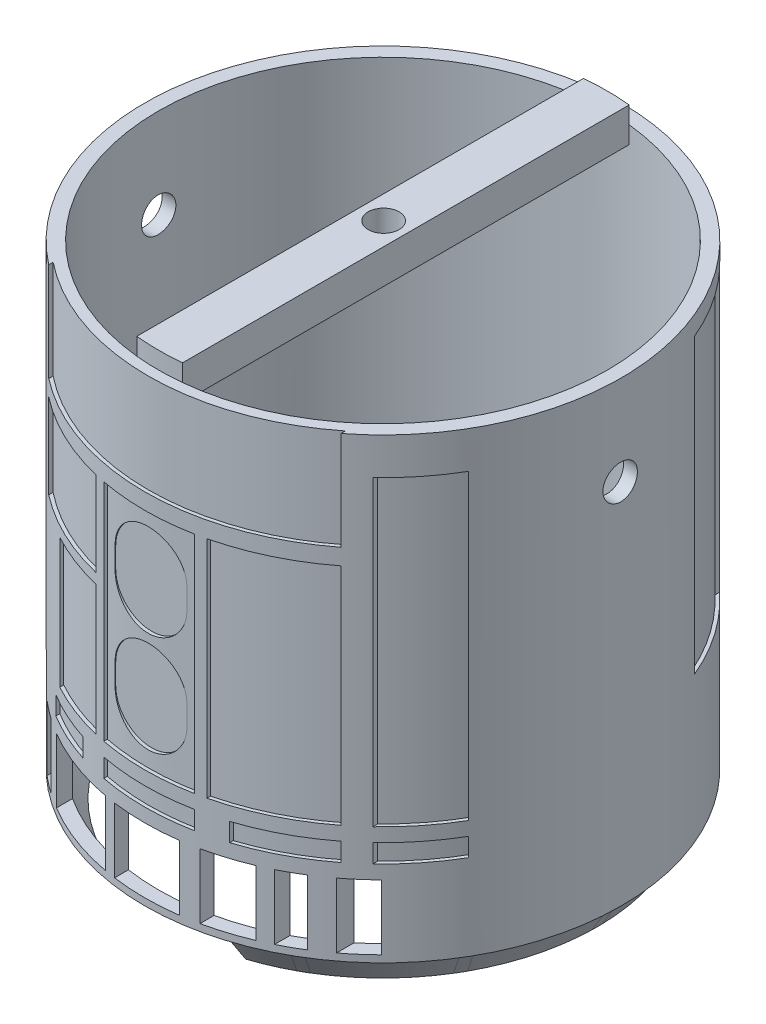
SolidWorks part; units mm, degrees
ref_plane "Front Plane" through (0, 0, 0) normal (0, 0, 1) x (1, 0, 0)
ref_plane "Top Plane" through (0, 0, 0) normal (0, 1, 0) x (1, 0, 0)
ref_plane "Right Plane" through (0, 0, 0) normal (1, 0, 0) x (0, 0, -1)
ref_plane "Plane1" through (0, 71.455, 0) normal (0, -1, 0) x (-1, 0, 0)
sketch "Sketch2" plane through (0, 71.455, 0) normal (0, -1, 0) x (-1, 0, 0)
  line L0 (-38.9651, -35.0313) -> (-38.9651, -151.6617) construction
  line L4 (-38.9651, -105.3401) -> (-38.9651, -128.5901) construction
  line L5 (-163.8451, -151.6283) -> (-163.8451, -35.0647) construction
  line L6 (-163.8451, -58.0901) -> (-163.8451, -81.3401) construction
  arc A2 (-38.9651, -35.0313) -> (-163.8451, -35.0647) centre (-101.3896, -93.3465) ccw construction
  circle A5 centre (-101.2592, -93.1749) radius 81.6374 construction
  circle A6 centre (-101.2592, -93.1749) radius 82.9074
  circle A7 centre (-101.2592, -93.1749) radius 87.9874
  dimension "D1" = 1.27
  dimension "D2" = 5.08
extrude "Boss-Extrude1" add sketch "Sketch2" against normal up to vertex (168.8629 mm away)
sketch "Sketch3" plane through (163.8451, 0, 0) normal (1, 0, 0) x (0, 0, -1)
  line L0 (-146.312, 80.955) -> (-146.312, 71.455) construction
  line L1 (-153.932, 82.225) -> (-107.1601, 82.225)
  line L2 (-153.932, 82.225) -> (-153.932, 68.28)
  line L3 (-153.932, 68.28) -> (-32.7482, 68.28)
  line L4 (-32.7482, 82.225) -> (-32.7482, 68.28)
  line L7 (-40.3682, 71.455) -> (-40.3682, 80.955) construction
  line L8 (-132.7773, 80.955) -> (-144.8088, 80.955) construction
  line L9 (-35.0647, 68.28) -> (-151.6283, 68.28) construction
  line L10 (-79.5201, 82.225) -> (-32.7482, 82.225)
  line L11 (-107.1601, 121.595) -> (-79.5201, 121.595)
  line L12 (-107.1601, 121.595) -> (-107.1601, 82.225)
  line L14 (-79.5201, 121.595) -> (-79.5201, 82.225)
  line L15 (-105.8901, 116.805) -> (-105.8901, 106.605) construction
  line L16 (-80.7901, 116.805) -> (-80.7901, 106.605) construction
  dimension "D1" = 1.27
  dimension "D2" = 7.62
  dimension "D3" = 7.62
  dimension "D4" = 1.27
  dimension "D5" = 1.27
  dimension "D6" = 39.37
extrude "Cut-Extrude1" [suppressed] cut sketch "Sketch3" against normal through all both
sketch "Sketch4" plane through (0, 240.3982, 0) normal (0, 1, 0) x (1, 0, 0)
  circle A2 centre (101.4962, -94.1217) radius 81.1277
  circle A3 centre (101.4962, -94.1217) radius 81.1277
  circle A5 centre (101.4962, -94.1217) radius 84.1757 construction
  dimension "D1" = 5.08
extrude "Cut-Extrude2" [suppressed] cut sketch "Sketch4" against normal through all both
fillet "Fillet1" [suppressed] radius 30.48
ref_plane "Body mid plane" through (101.4051, -9.1621, 1.5034) normal (1, 0, 0) x (0, 0, -1)
sketch "Sketch7" plane through (101.4051, -9.1621, 1.5034) normal (1, 0, 0) x (0, 0, -1)
  line L0 (-5.8069, 80.6171) -> (-12.6369, 69.6961)
  line L1 (-91.8367, 60.9602) -> (-91.8367, 159.3782) construction
  point P5 (-10.4132, 69.2196)
  point P6 (-5.8069, 80.6171)
  point P7 (-12.6369, 69.6961)
  point P9 (-91.8367, 60.9602)
revolve "Revolve-Thin1" add sketch "Sketch7" angle 360 about L1
sketch "Sketch9" plane through (0, 240.318, 0) normal (0, 1, 0) x (1, 0, 0)
  circle A0 centre (101.2592, -93.1749) radius 87.9874 construction
  point P0 (101.2592, -181.1623)
ref_plane "Body front plane" through (101.2592, 240.318, 181.1623) normal (0, 0, 1) x (1, 0, 0)
sketch "Sketch8" plane through (101.2592, 240.318, 181.1623) normal (0, 0, 1) x (1, 0, 0)
  line L1 (-53.975, 0) -> (53.975, 0)
  line L2 (-53.975, 0) -> (-53.975, -36.4031)
  line L3 (-53.975, -36.4031) -> (53.975, -36.4031)
  line L4 (53.975, 0) -> (53.975, -36.4031)
  line L5 (-75.9451, -13.6762) -> (-60.325, -13.6762)
  line L6 (-75.9451, -13.6762) -> (-75.9451, -125.3442)
  line L7 (-75.9451, -125.3442) -> (-60.325, -125.3442)
  line L8 (-60.325, -13.6762) -> (-60.325, -125.3442)
  line L9 (60.325, -13.6762) -> (75.9451, -13.6762)
  line L10 (60.325, -13.6762) -> (60.325, -125.3442)
  line L11 (60.325, -125.3442) -> (75.9451, -125.3442)
  line L12 (75.9451, -13.6762) -> (75.9451, -125.3442)
  line L13 (53.975, -42.3499) -> (20.5317, -42.3499)
  line L14 (53.975, -42.3499) -> (53.975, -125.3442)
  line L15 (53.975, -125.3442) -> (20.5317, -125.3442)
  line L16 (20.5317, -42.3499) -> (20.5317, -125.3442)
  line L17 (-53.975, -42.3499) -> (-20.5317, -42.3499)
  line L18 (-53.975, -42.3499) -> (-53.975, -73.6192)
  line L19 (-53.975, -73.6192) -> (-20.5317, -73.6192)
  line L20 (-20.5317, -42.3499) -> (-20.5317, -73.6192)
  line L21 (-16.7217, -42.3499) -> (16.7217, -42.3499)
  line L22 (-16.7217, -42.3499) -> (-16.7217, -125.3442)
  line L23 (-16.7217, -125.3442) -> (16.7217, -125.3442)
  line L24 (16.7217, -42.3499) -> (16.7217, -125.3442)
  line L25 (-20.5317, -77.3529) -> (-42.14, -77.3529)
  line L26 (-20.5317, -77.3529) -> (-20.5317, -125.3442)
  line L27 (-20.5317, -125.3442) -> (-42.14, -125.3442)
  line L28 (-42.14, -77.3529) -> (-42.14, -125.3442)
  line L29 (60.325, -130.4242) -> (75.9451, -130.4242)
  line L30 (60.325, -130.4242) -> (60.325, -137.2396)
  line L31 (86.2077, 0) -> (-86.2077, 0) construction
  line L33 (60.325, -137.2396) -> (75.9451, -137.2396)
  line L34 (75.9451, -130.4242) -> (75.9451, -137.2396)
  line L35 (53.975, -130.4242) -> (27.0779, -130.4242)
  line L36 (53.975, -130.4242) -> (53.975, -137.2396)
  line L37 (53.975, -137.2396) -> (27.0779, -137.2396)
  line L38 (27.0779, -130.4242) -> (27.0779, -137.2396)
  line L39 (-16.7217, -130.4242) -> (16.7217, -130.4242)
  line L40 (-16.7217, -130.4242) -> (-16.7217, -137.2396)
  line L41 (-16.7217, -137.2396) -> (16.7217, -137.2396)
  line L42 (16.7217, -130.4242) -> (16.7217, -137.2396)
  line L43 (-27.1833, -130.4242) -> (-45.5325, -130.4242)
  line L44 (-27.1833, -130.4242) -> (-27.1833, -137.2396)
  line L45 (-27.1833, -137.2396) -> (-45.5325, -137.2396)
  line L46 (-45.5325, -130.4242) -> (-45.5325, -137.2396)
  line L47 (61.9414, -142.3196) -> (53.0289, -142.3196)
  line L48 (61.9414, -142.3196) -> (61.9414, -166.2789)
  line L49 (61.9414, -166.2789) -> (53.0289, -166.2789)
  line L50 (53.0289, -142.3196) -> (53.0289, -166.2789)
  line L51 (46.7378, -142.3196) -> (38.8738, -142.3196)
  line L52 (46.7378, -142.3196) -> (46.7378, -166.2789)
  line L53 (46.7378, -166.2789) -> (38.8738, -166.2789)
  line L54 (38.8738, -142.3196) -> (38.8738, -166.2789)
  line L55 (18.4276, -142.3196) -> (34.1555, -142.3196)
  line L56 (18.4276, -142.3196) -> (18.4276, -166.2789)
  line L57 (18.4276, -166.2789) -> (34.1555, -166.2789)
  line L58 (34.1555, -142.3196) -> (34.1555, -166.2789)
  line L59 (-11.9797, -142.3196) -> (11.9797, -142.3196)
  line L60 (-11.9797, -142.3196) -> (-11.9797, -166.2789)
  line L61 (-11.9797, -166.2789) -> (11.9797, -166.2789)
  line L62 (11.9797, -142.3196) -> (11.9797, -166.2789)
  line L64 (82.9074, 0) -> (-82.9074, 0) construction
  point P28 (0, 0)
  point P30 (0, 0)
  point P31 (0, 0)
  point P34 (0, -36.4031)
  point P35 (0, -42.3499)
  point P71 (0, -142.3196)
  point P72 (0, -125.3442)
  point P73 (0, 0)
  point P74 (0, 0)
  point P75 (0, 0)
  point P76 (0, 0)
  dimension "D1" = 3.81
  dimension "D2" = 5.08
  dimension "D3" = 6.35
  dimension "D4" = 6.35
  dimension "D5" = 107.95
  dimension "D6" = 5.08
extrude "Cut-Extrude6" cut sketch "Sketch8" against normal offset from surface (20.1154 mm away) 3.81
sketch "Sketch10" plane through (101.2592, 240.318, 181.1623) normal (0, 0, 1) x (1, 0, 0)
  line L0 (-13.2648, -61.3999) -> (-13.2648, -69.0199)
  line L1 (13.2648, -69.0199) -> (13.2648, -61.3999)
  line L2 (-16.7217, -42.3499) -> (16.7217, -42.3499) construction
  line L3 (-13.2648, -98.6742) -> (-13.2648, -106.2942)
  line L4 (13.2648, -106.2942) -> (13.2648, -98.6742)
  line L5 (16.7217, -125.3442) -> (-16.7217, -125.3442) construction
  arc A0 (-13.2648, -69.0199) -> (13.2648, -69.0199) centre (0, -69.0199) ccw
  arc A1 (13.2648, -61.3999) -> (-13.2648, -61.3999) centre (0, -61.3999) ccw
  arc A2 (-13.2648, -106.2942) -> (13.2648, -106.2942) centre (0, -106.2942) ccw
  arc A3 (13.2648, -98.6742) -> (-13.2648, -98.6742) centre (0, -98.6742) ccw
  point P6 (-12.5748, -63.8402)
  point P7 (0, 0)
  point P10 (0, -42.3499)
  point P17 (0, 0)
  point P18 (0, 0)
  dimension "D1" = 19.05
  dimension "D2" = 19.05
  dimension "D3" = 7.62
  dimension "D4" = 7.62
extrude "Cut-Extrude10" cut sketch "Sketch10" against normal blind 2.54
ref_plane "Plane4" through (101.2592, 240.318, 5.1875) normal (0, 0, -1) x (-1, 0, 0)
sketch "Sketch11" plane through (101.2592, 240.318, 5.1875) normal (0, 0, -1) x (-1, 0, 0)
  line L0 (-87.9874, 0) -> (87.9874, 0) construction
  line L2 (-52.8618, -6.9317) -> (55.2346, -6.9317)
  line L3 (-52.8618, -6.9317) -> (-52.8618, -47.9115)
  line L4 (-52.8618, -47.9115) -> (55.2346, -47.9115)
  line L5 (55.2346, -6.9317) -> (55.2346, -47.9115)
  line L6 (-52.8618, -52.1063) -> (-19.6262, -52.1063)
  line L7 (-52.8618, -52.1063) -> (-52.8618, -115.028)
  line L8 (-52.8618, -115.028) -> (-19.6262, -115.028)
  line L9 (-19.6262, -52.1063) -> (-19.6262, -115.028)
  line L10 (-13.1727, -52.1063) -> (22.967, -52.1063)
  line L11 (-13.1727, -52.1063) -> (-13.1727, -115.028)
  line L12 (-13.1727, -115.028) -> (22.967, -115.028)
  line L13 (22.967, -52.1063) -> (22.967, -115.028)
  line L14 (29.7432, -52.1063) -> (55.2346, -52.1063)
  line L15 (29.7432, -52.1063) -> (29.7432, -115.028)
  line L16 (29.7432, -115.028) -> (55.2346, -115.028)
  line L17 (55.2346, -52.1063) -> (55.2346, -115.028)
  line L18 (-52.8618, -122.1269) -> (-19.6262, -122.1269)
  line L19 (-52.8618, -122.1269) -> (-52.8618, -131.4845)
  line L20 (-52.8618, -131.4845) -> (-19.6262, -131.4845)
  line L21 (-19.6262, -122.1269) -> (-19.6262, -131.4845)
  line L22 (-13.1727, -122.1269) -> (22.967, -122.1269)
  line L23 (-13.1727, -122.1269) -> (-13.1727, -131.4845)
  line L24 (-13.1727, -131.4845) -> (22.967, -131.4845)
  line L25 (22.967, -122.1269) -> (22.967, -131.4845)
  line L26 (29.7432, -122.1269) -> (55.2346, -122.1269)
  line L27 (29.7432, -122.1269) -> (29.7432, -131.4845)
  line L28 (29.7432, -131.4845) -> (55.2346, -131.4845)
  line L29 (55.2346, -122.1269) -> (55.2346, -131.4845)
  line L30 (63.3015, -6.9317) -> (81.694, -6.9317)
  line L31 (63.3015, -6.9317) -> (63.3015, -115.028)
  line L32 (63.3015, -115.028) -> (81.694, -115.028)
  line L33 (81.694, -6.9317) -> (81.694, -115.028)
  line L34 (-59.638, -6.9317) -> (-81.2572, -6.9317)
  line L35 (-59.638, -6.9317) -> (-59.638, -115.028)
  line L36 (-59.638, -115.028) -> (-81.2572, -115.028)
  line L37 (-81.2572, -6.9317) -> (-81.2572, -115.028)
  line L38 (63.3015, -122.1269) -> (81.694, -122.1269)
  line L39 (63.3015, -122.1269) -> (63.3015, -131.4845)
  line L40 (63.3015, -131.4845) -> (81.694, -131.4845)
  line L41 (81.694, -122.1269) -> (81.694, -131.4845)
extrude "Cut-Extrude11" cut sketch "Sketch11" against normal offset from surface (21.1365 mm away) 3.81
sketch "Sketch12" plane through (0, 71.455, 0) normal (0, -1, 0) x (-1, 0, 0)
  line L0 (-176.9337, -52.1508) -> (-175.0545, -48.8959)
  line L1 (-187.4094, -95.4334) -> (-180.5875, -95.4334)
  line L2 (-187.4094, -95.4334) -> (-187.4094, -91.675)
  line L3 (-187.4094, -91.675) -> (-180.5875, -91.675)
  line L4 (-180.5875, -95.4334) -> (-180.5875, -91.675)
  line L5 (-176.9337, -52.1508) -> (-171.0257, -55.5618)
  line L6 (-171.0257, -55.5618) -> (-169.1465, -52.3069)
  line L7 (-175.0545, -48.8959) -> (-169.1465, -52.3069)
  line L8 (-146.2202, -19.9048) -> (-142.9652, -18.0256)
  line L9 (-146.2202, -19.9048) -> (-142.8092, -25.8128)
  line L10 (-142.8092, -25.8128) -> (-139.5543, -23.9336)
  line L11 (-142.9652, -18.0256) -> (-139.5543, -23.9336)
  line L12 (-103.4985, -7.3358) -> (-99.74, -7.3358)
  line L13 (-103.4985, -7.3358) -> (-103.4985, -14.1577)
  line L14 (-103.4985, -14.1577) -> (-99.74, -14.1577)
  line L15 (-99.74, -7.3358) -> (-99.74, -14.1577)
  line L16 (-60.2159, -17.8115) -> (-56.9609, -19.6907)
  line L17 (-60.2159, -17.8115) -> (-63.6269, -23.7195)
  line L18 (-63.6269, -23.7195) -> (-60.3719, -25.5987)
  line L19 (-56.9609, -19.6907) -> (-60.3719, -25.5987)
  line L20 (-27.9699, -48.525) -> (-26.0907, -51.78)
  line L21 (-27.9699, -48.525) -> (-33.8779, -51.936)
  line L22 (-33.8779, -51.936) -> (-31.9986, -55.1909)
  line L23 (-26.0907, -51.78) -> (-31.9986, -55.1909)
  line L24 (-15.4008, -91.2467) -> (-15.4008, -95.0052)
  line L25 (-15.4008, -91.2467) -> (-22.2228, -91.2467)
  line L26 (-22.2228, -91.2467) -> (-22.2228, -95.0052)
  line L27 (-15.4008, -95.0052) -> (-22.2228, -95.0052)
  line L28 (-25.8765, -134.5293) -> (-27.7558, -137.7843)
  line L29 (-25.8765, -134.5293) -> (-31.7845, -131.1183)
  line L30 (-31.7845, -131.1183) -> (-33.6638, -134.3733)
  line L31 (-27.7558, -137.7843) -> (-33.6638, -134.3733)
  line L32 (-56.5901, -166.7753) -> (-59.845, -168.6546)
  line L33 (-56.5901, -166.7753) -> (-60.0011, -160.8673)
  line L34 (-60.0011, -160.8673) -> (-63.256, -162.7466)
  line L35 (-59.845, -168.6546) -> (-63.256, -162.7466)
  line L36 (-99.3118, -179.3444) -> (-103.0703, -179.3444)
  line L37 (-99.3118, -179.3444) -> (-99.3118, -172.5224)
  line L38 (-99.3118, -172.5224) -> (-103.0703, -172.5224)
  line L39 (-103.0703, -179.3444) -> (-103.0703, -172.5224)
  line L40 (-142.5944, -168.8687) -> (-145.8493, -166.9894)
  line L41 (-142.5944, -168.8687) -> (-139.1834, -162.9607)
  line L42 (-139.1834, -162.9607) -> (-142.4383, -161.0814)
  line L43 (-145.8493, -166.9894) -> (-142.4383, -161.0814)
  line L44 (-174.8404, -138.1551) -> (-176.7196, -134.9002)
  line L45 (-174.8404, -138.1551) -> (-168.9324, -134.7442)
  line L46 (-168.9324, -134.7442) -> (-170.8116, -131.4892)
  line L47 (-176.7196, -134.9002) -> (-170.8116, -131.4892)
  circle A0 centre (-101.4051, -93.3401) radius 86.0298 construction
  circle A1 centre (-101.4051, -93.3401) radius 79.1999 construction
  point P55 (-101.4051, -93.3401)
  dimension "D1" = 12
split line "Split Line2"
ref_plane "Plane5" through (204.47, 0, 0) normal (1, 0, 0) x (0, 0, -1)
sketch "Sketch13" plane through (204.47, 0, 0) normal (1, 0, 0) x (0, 0, -1)
  circle A0 centre (-93.3401, 207.1621) radius 6.35 construction
  circle A1 centre (-93.3401, 207.1621) radius 6.35
extrude "Cut-Extrude12" cut sketch "Sketch13" against normal through all both
sketch "Sketch15" plane through (0, 240.318, 0) normal (0, 1, 0) x (1, 0, 0)
  line L1 (101.2592, -5.1875) -> (101.2592, -181.1623) construction
  line L2 (109.7206, -10.7004) -> (109.7206, -175.6494)
  line L3 (92.7978, -10.7004) -> (92.7978, -175.6494)
  circle A5 centre (101.2592, -93.1749) radius 82.9074 construction
  arc A6 (92.7978, -175.6494) -> (109.7206, -175.6494) centre (101.2592, -93.1749) ccw
  arc A7 (155.2342, -162.6622) -> (47.2842, -162.6622) centre (101.2592, -93.1749) ccw construction
  arc A8 (109.7206, -10.7004) -> (92.7978, -10.7004) centre (101.2592, -93.1749) ccw
extrude "Boss-Extrude2" add sketch "Sketch15" along normal blind 6.35 and the other way blind 6.35
sketch "Sketch16" plane through (0, 246.668, 0) normal (0, 1, 0) x (1, 0, 0)
  line L0 (101.2592, -10.2675) -> (101.4051, -93.0901) construction
  line L1 (99.9618, -93.0901) -> (102.8485, -93.0901) construction
  arc A0 (109.7206, -10.7004) -> (92.7978, -10.7004) centre (101.2592, -93.1749) ccw construction
  circle A1 centre (101.4051, -93.0901) radius 5.715
extrude "Cut-Extrude14" cut sketch "Sketch16" against normal up to vertex
sketch "Sketch17" plane through (101.2592, 240.318, 181.1623) normal (0, 0, 1) x (1, 0, 0)
  line L0 (61.9414, -166.2789) -> (61.9414, -142.3196) construction
  line L1 (53.0289, -142.3196) -> (61.9414, -142.3196) construction
  line L2 (53.0289, -142.3196) -> (53.0289, -166.2789) construction
  line L3 (61.9414, -166.2789) -> (53.0289, -166.2789) construction
  line L4 (46.7378, -166.2789) -> (46.7378, -142.3196) construction
  line L5 (38.8738, -142.3196) -> (46.7378, -142.3196) construction
  line L6 (38.8738, -142.3196) -> (38.8738, -166.2789) construction
  line L7 (46.7378, -166.2789) -> (38.8738, -166.2789) construction
  line L8 (18.4276, -142.3196) -> (18.4276, -166.2789) construction
  line L9 (34.1555, -166.2789) -> (18.4276, -166.2789) construction
  line L10 (34.1555, -166.2789) -> (34.1555, -142.3196) construction
  line L11 (18.4276, -142.3196) -> (34.1555, -142.3196) construction
  line L12 (-11.9797, -142.3196) -> (-11.9797, -166.2789) construction
  line L13 (11.9797, -166.2789) -> (-11.9797, -166.2789) construction
  line L14 (11.9797, -166.2789) -> (11.9797, -142.3196) construction
  line L15 (-11.9797, -142.3196) -> (11.9797, -142.3196) construction
  line L16 (61.9414, -166.2789) -> (61.9414, -142.3196)
  line L17 (53.0289, -142.3196) -> (61.9414, -142.3196)
  line L18 (53.0289, -142.3196) -> (53.0289, -166.2789)
  line L19 (61.9414, -166.2789) -> (53.0289, -166.2789)
  line L20 (46.7378, -166.2789) -> (46.7378, -142.3196)
  line L21 (38.8738, -142.3196) -> (46.7378, -142.3196)
  line L22 (38.8738, -142.3196) -> (38.8738, -166.2789)
  line L23 (46.7378, -166.2789) -> (38.8738, -166.2789)
  line L24 (18.4276, -142.3196) -> (18.4276, -166.2789)
  line L25 (34.1555, -166.2789) -> (18.4276, -166.2789)
  line L26 (34.1555, -166.2789) -> (34.1555, -142.3196)
  line L27 (18.4276, -142.3196) -> (34.1555, -142.3196)
  line L28 (-11.9797, -142.3196) -> (-11.9797, -166.2789)
  line L29 (11.9797, -166.2789) -> (-11.9797, -166.2789)
  line L30 (11.9797, -166.2789) -> (11.9797, -142.3196)
  line L31 (-11.9797, -142.3196) -> (11.9797, -142.3196)
  line L33 (-15.9574, -142.3196) -> (-45.0907, -142.3196)
  line L34 (-15.9574, -142.3196) -> (-15.9574, -166.2789)
  line L35 (-15.9574, -166.2789) -> (-45.0907, -166.2789)
  line L36 (-45.0907, -142.3196) -> (-45.0907, -166.2789)
  line L37 (-50.9683, -142.3196) -> (-57.1678, -142.3196)
  line L38 (-50.9683, -142.3196) -> (-50.9683, -166.2789)
  line L39 (-50.9683, -166.2789) -> (-57.1678, -166.2789)
  line L40 (-57.1678, -142.3196) -> (-57.1678, -166.2789)
  ellipse E0 centre (-44.4713, -164.8629) end of major axis (-44.4713, -166.4629) minor radius 1.3304 (-45.8016, -164.8629) -> (-43.1409, -164.8629) ccw construction
  ellipse E1 centre (-56.641, -164.8629) end of major axis (-56.641, -166.4629) minor radius 1.1314 (-57.7724, -164.8629) -> (-55.5096, -164.8629) ccw construction
extrude "Cut-Extrude16" cut sketch "Sketch17" against normal up to surface (32.8793 mm away)
sketch "Sketch18" plane through (101.2592, 240.318, 181.1623) normal (0, 0, 1) x (1, 0, 0)
  line L0 (38.2951, -179.784) -> (1.811, -179.784) construction
  line L1 (-24.4558, -168.8629) -> (24.7477, -168.8629)
  line L2 (-24.4558, -168.8629) -> (-24.4558, -179.784)
  line L3 (-24.4558, -179.784) -> (24.7477, -179.784)
  line L4 (24.7477, -168.8629) -> (24.7477, -179.784)
  line L5 (24.7477, -168.8629) -> (24.7477, -159.3629) construction
  line L6 (-24.4558, -168.8629) -> (-24.4558, -159.3629) construction
  line L7 (-1.9474, -168.8629) -> (41.3352, -168.8629) construction
  point P11 (24.7477, -168.8629)
extrude "Cut-Extrude17" cut sketch "Sketch18" against normal up to surface (8.5165 mm away)
